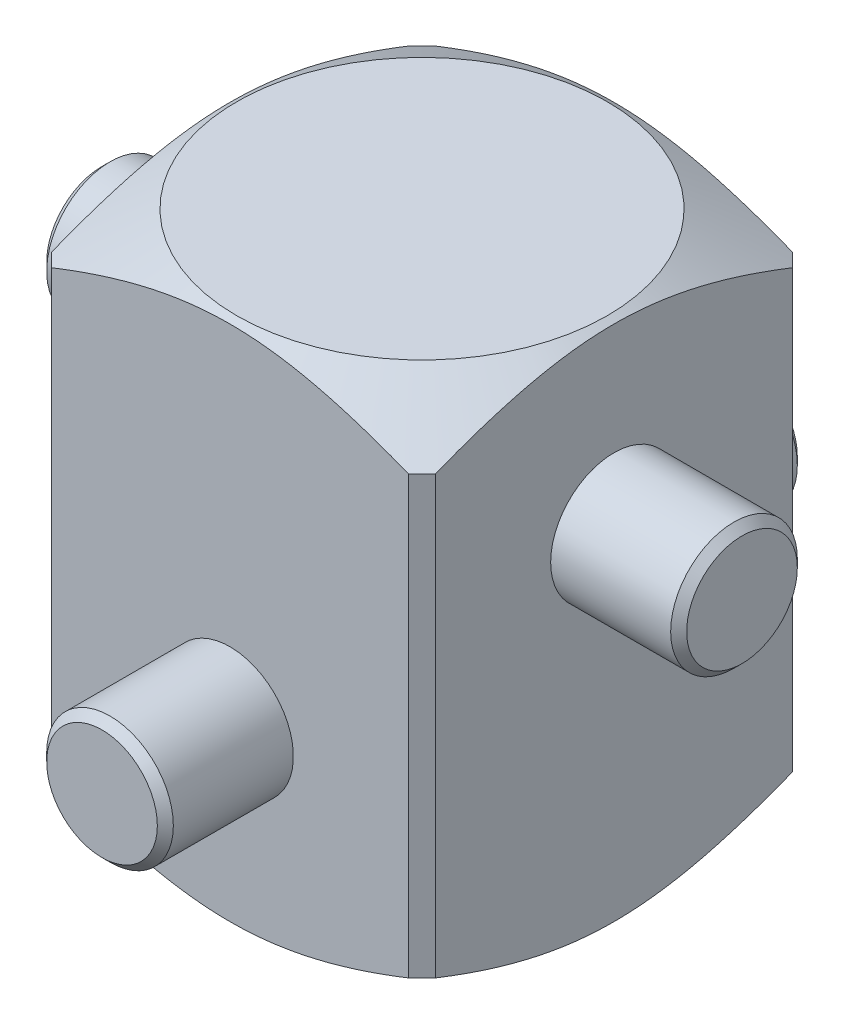
SolidWorks part; units mm, degrees
material "Plain Carbon Steel"
ref_plane "Front Plane" through (0, 0, 0) normal (0, 0, 1) x (1, 0, 0)
ref_plane "Top Plane" through (0, 0, 0) normal (0, 1, 0) x (1, 0, 0)
ref_plane "Right Plane" through (0, 0, 0) normal (1, 0, 0) x (0, 0, -1)
sketch "Sketch1" plane through (0, 0, 0) normal (0, 1, 0) x (1, 0, 0)
  line L1 (-7.2, 7.2) -> (7.2, 7.2)
  line L2 (-7.2, 7.2) -> (-7.2, -7.2)
  line L3 (-7.2, -7.2) -> (7.2, -7.2)
  line L4 (7.2, 7.2) -> (7.2, -7.2)
  line L5 (-7.2, 7.2) -> (7.2, -7.2) construction
  line L6 (-7.2, -7.2) -> (7.2, 7.2) construction
  point P0 (0, 0)
  dimension "D1" = 14.4
extrude "Boss-Extrude1" add sketch "Sketch1" along normal blind 19.7
ref_axis "Axis1" through (0, 20.685, 0) along (0, -1, 0)
sketch "Sketch2" plane through (0, 0, 0) normal (0, 0, 1) x (1, 0, 0)
  line L0 (-6.95, 19.7) -> (-16.09, 19.7)
  line L1 (-7.2, 19.7) -> (7.2, 19.7) construction
  line L2 (-16.09, 19.7) -> (-16.09, 0)
  line L3 (-16.09, 0) -> (-6.95, 0)
  line L4 (-7.2, 0) -> (7.2, 0) construction
  line L5 (-6.95, 19.7) -> (-13.55, 15.8895)
  line L6 (-13.55, 15.8895) -> (-13.55, 3.8105)
  line L7 (-13.55, 3.8105) -> (-6.95, 0)
  line L8 (-7.2, 19.7) -> (-7.2, 0) construction
  point P10 (-13.55, 9.85)
  point P13 (-7.2, 9.85)
  dimension "D1" = 0.25
  dimension "D2" = 6.35
  dimension "D3" = 2.54
  dimension "D4" = 30
  dimension "D5" = 30
revolve "Cut-Revolve1" cut sketch "Sketch2" angle 360 about axis through (0, 20.685, 0) along (0, -1, 0)
sketch "Sketch3" plane through (0, 0, 0) normal (0, 0, 1) x (1, 0, 0)
  line L0 (0, 20.685) -> (0, -0.985) construction
  circle A0 centre (0, 6.7) radius 2.375
  dimension "D1" = 4.75
  dimension "D2" = 6.7
extrude "Boss-Extrude2" add sketch "Sketch3" along normal mid plane 24
sketch "Sketch4" plane through (0, 0, 0) normal (1, 0, 0) x (0, 0, -1)
  line L0 (0, 20.685) -> (0, -0.985) construction
  line L1 (6.95, 19.7) -> (-6.95, 19.7) construction
  circle A0 centre (0, 13) radius 2.375
  dimension "D1" = 4.75
  dimension "D2" = 6.7
extrude "Boss-Extrude3" add sketch "Sketch4" along normal mid plane 24
chamfer "Chamfer1" distance 0.3 angle 45 4 edges at (2.375, 6.7, -12) (-12, 13, -2.375) (12, 13, -2.375) (2.375, 6.7, 12)
chamfer "Chamfer2" distance 0.5 angle 45 4 edges at (7.2, 9.85, 7.2) (7.2, 9.85, -7.2) (-7.2, 9.85, 7.2) (-7.2, 9.85, -7.2)
scale "Scale1" scale about centroid uniform scaling yes scale factor 0.49
